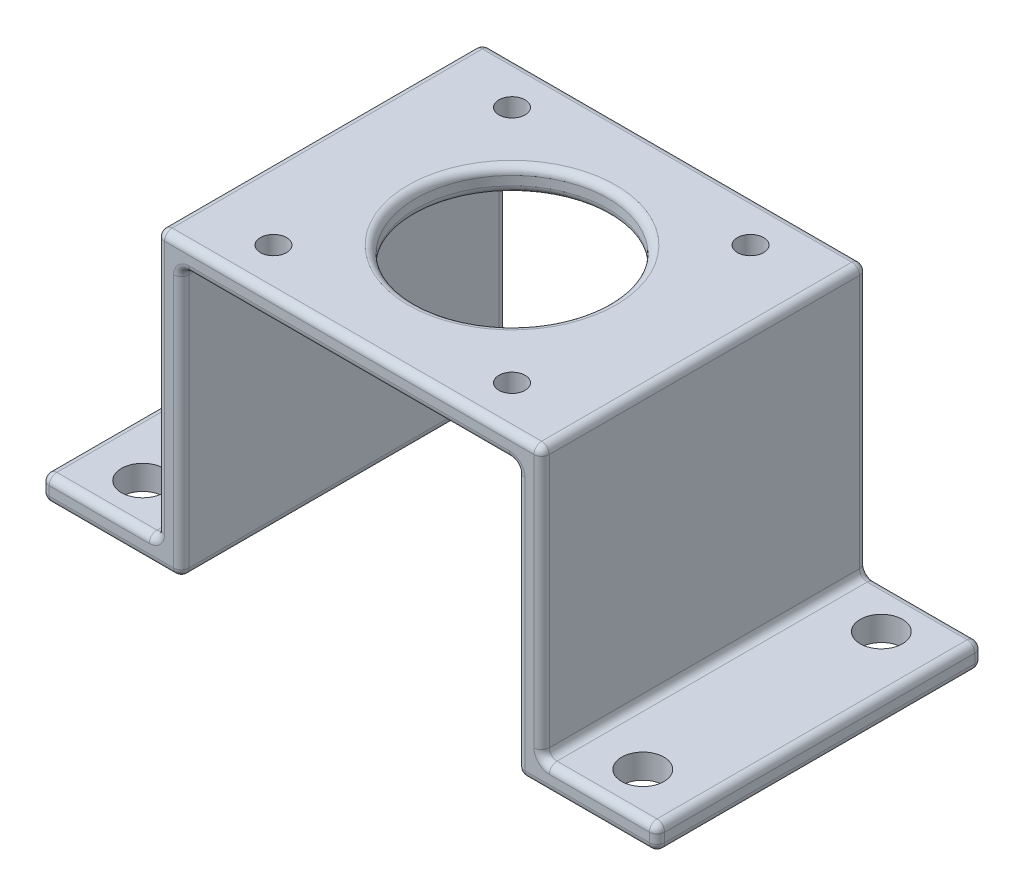
SolidWorks part; units mm, degrees
ref_plane "Front Plane" through (0, 0, 0) normal (0, 0, 1) x (1, 0, 0)
ref_plane "Top Plane" through (0, 0, 0) normal (0, 1, 0) x (1, 0, 0)
ref_plane "Right Plane" through (0, 0, 0) normal (1, 0, 0) x (0, 0, -1)
sketch "Sketch1" plane through (0, 0, 0) normal (0, 1, 0) x (1, 0, 0)
  line L1 (25, -21.15) -> (-25, -21.15)
  line L2 (25, -21.15) -> (25, 21.15)
  line L3 (25, 21.15) -> (-25, 21.15)
  line L4 (-25, -21.15) -> (-25, 21.15)
  line L5 (25, -21.15) -> (-25, 21.15) construction
  line L6 (25, 21.15) -> (-25, -21.15) construction
  line L7 (15.5, -15.5) -> (-15.5, -15.5) construction
  line L8 (15.5, -15.5) -> (15.5, 15.5) construction
  line L9 (15.5, 15.5) -> (-15.5, 15.5) construction
  line L10 (-15.5, -15.5) -> (-15.5, 15.5) construction
  line L11 (15.5, -15.5) -> (-15.5, 15.5) construction
  line L12 (15.5, 15.5) -> (-15.5, -15.5) construction
  circle A0 centre (0, 0) radius 12.5
  circle A1 centre (-15.5, 15.5) radius 1.7
  circle A2 centre (15.5, 15.5) radius 1.7
  circle A3 centre (15.5, -15.5) radius 1.7
  circle A4 centre (-15.5, -15.5) radius 1.7
  point P0 (0, 0)
  dimension "D3" = 25
  dimension "D5" = 3.4
  dimension "D1" = 50
  dimension "D2" = 42.3
  dimension "D4" = 31
extrude "Boss-Extrude1" add sketch "Sketch1" along normal blind 3.175
sketch "Sketch2" plane through (0, 0, 0) normal (0, -1, 0) x (1, 0, 0)
  line L0 (25, -21.15) -> (-25, -21.15) construction
  line L1 (-25, 21.15) -> (-21.825, 21.15)
  line L2 (-25, 21.15) -> (-25, -21.15)
  line L3 (-25, -21.15) -> (-21.825, -21.15)
  line L4 (-21.825, 21.15) -> (-21.825, -21.15)
  line L5 (-25, 21.15) -> (25, 21.15) construction
  line L6 (25, -21.15) -> (21.825, -21.15)
  line L7 (25, -21.15) -> (25, 21.15)
  line L8 (25, 21.15) -> (21.825, 21.15)
  line L9 (21.825, -21.15) -> (21.825, 21.15)
  dimension "D1" = 3.175
extrude "Boss-Extrude2" add sketch "Sketch2" along normal blind 35
sketch "Sketch3" plane through (0, -35, 0) normal (0, -1, 0) x (1, 0, 0)
  line L0 (-25, -21.15) -> (-21.825, -21.15) construction
  line L1 (-25, 21.15) -> (-40, 21.15)
  line L2 (-25, 21.15) -> (-25, -21.15)
  line L3 (-25, -21.15) -> (-40, -21.15)
  line L4 (-40, 21.15) -> (-40, -21.15)
  line L5 (25, 21.15) -> (40, 21.15)
  line L6 (25, 21.15) -> (25, -21.15)
  line L7 (25, -21.15) -> (40, -21.15)
  line L8 (40, 21.15) -> (40, -21.15)
  line L9 (-32.5, 21.15) -> (-32.5, 15.5) construction
  line L10 (-32.5, 15.5) -> (-32.5, -15.5) construction
  line L11 (-32.5, -15.5) -> (-32.5, -21.15) construction
  line L12 (32.5, -21.15) -> (32.5, -15.5) construction
  line L13 (32.5, -15.5) -> (32.5, 15.5) construction
  line L14 (32.5, 15.5) -> (32.5, 21.15) construction
  circle A0 centre (-32.5, 15.5) radius 2.75
  circle A1 centre (-32.5, -15.5) radius 2.75
  circle A2 centre (32.5, -15.5) radius 2.75
  circle A3 centre (32.5, 15.5) radius 2.75
  dimension "D3" = 5.5
  dimension "D1" = 15
  dimension "D2" = 31
extrude "Boss-Extrude3" add sketch "Sketch3" against normal blind 3.175
fillet "Fillet1" radius 1 36 edges at (0, 3.175, 21.15) (32.5, -31.825, 21.15) (30.9125, -35, 21.15) (0, 0, 21.15) (-30.9125, -35, 21.15) (-32.5, -31.825, 21.15) (0, 3.175, -21.15) (-32.5, -31.825, -21.15) (-30.9125, -35, -21.15) (0, 0, -21.15) (30.9125, -35, -21.15) (32.5, -31.825, -21.15) (-40, -33.4125, -21.15) (-40, -31.825, 0) (-40, -33.4125, 21.15) (-40, -35, 0) (40, -33.4125, 21.15) (40, -31.825, 0) (40, -33.4125, -21.15) (40, -35, 0) (21.825, -17.5, 21.15) (21.825, 0, 0) (21.825, -35, 0) (21.825, -17.5, -21.15) (-21.825, -17.5, -21.15) (-21.825, -35, 0) (-21.825, -17.5, 21.15) (-21.825, 0, 0) (-25, 3.175, 0) (-25, -14.325, 21.15) (-25, -31.825, 0) (-25, -14.325, -21.15) (25, 3.175, 0) (25, -14.325, -21.15) (25, -31.825, 0) (25, -14.325, 21.15)
fillet "Fillet2" radius 1 2 edges at (0, 0, 12.5) (0, 3.175, 12.5)
